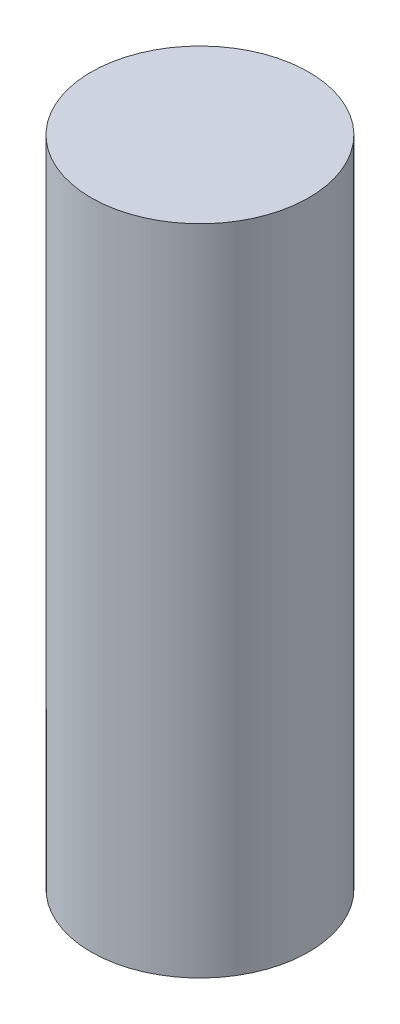
SolidWorks part; units mm, degrees
material "AISI 1045 Steel, cold drawn"
ref_plane "Front Plane" through (0, 0, 0) normal (0, 0, 1) x (1, 0, 0)
ref_plane "Top Plane" through (0, 0, 0) normal (0, 1, 0) x (1, 0, 0)
ref_plane "Right Plane" through (0, 0, 0) normal (1, 0, 0) x (0, 0, -1)
sketch "Sketch1" plane through (0, 0, 0) normal (0, 1, 0) x (1, 0, 0)
  circle A0 centre (0, 0) radius 25
extrude "Boss-Extrude1" add sketch "Sketch1" along normal blind 150
